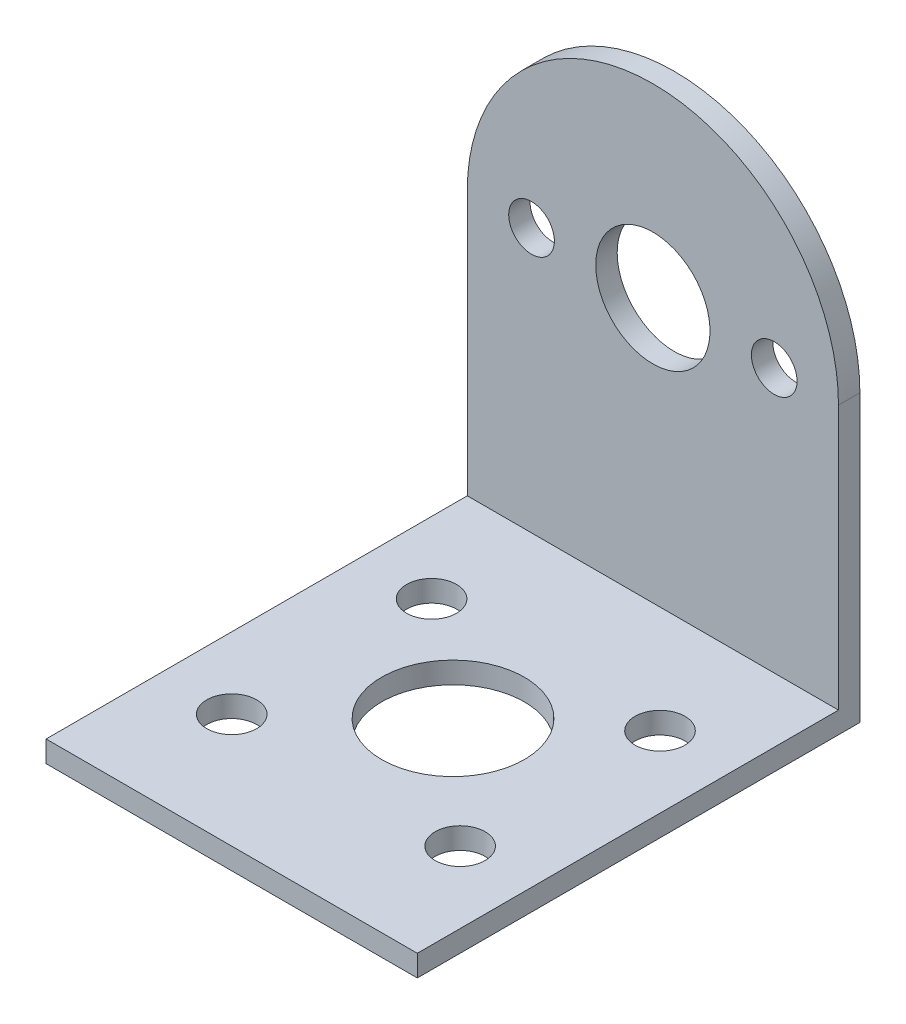
SolidWorks part; units mm, degrees
ref_plane "前视基准面" through (0, 0, 0) normal (0, 0, 1) x (1, 0, 0)
ref_plane "上视基准面" through (0, 0, 0) normal (0, 1, 0) x (1, 0, 0)
ref_plane "右视基准面" through (0, 0, 0) normal (1, 0, 0) x (0, 0, -1)
other "Configuration Table"
sketch "草图1" plane through (0, 0, 0) normal (0, 1, 0) x (1, 0, 0)
  line L1 (-13, -15.5) -> (13, -15.5)
  line L2 (-13, -15.5) -> (-13, 15.5)
  line L3 (-13, 15.5) -> (13, 15.5)
  line L4 (13, -15.5) -> (13, 15.5)
  line L5 (-13, -15.5) -> (13, 15.5) construction
  line L6 (-13, 15.5) -> (13, -15.5) construction
  line L7 (-8, -7.5) -> (8, -7.5) construction
  line L8 (-8, -7.5) -> (-8, 6.5) construction
  line L9 (-8, 6.5) -> (8, 6.5) construction
  line L10 (8, -7.5) -> (8, 6.5) construction
  line L11 (-8, -7.5) -> (8, 6.5) construction
  line L12 (-8, 6.5) -> (8, -7.5) construction
  circle A0 centre (0, 0) radius 5
  circle A1 centre (-8, 6.5) radius 1.75
  circle A2 centre (8, 6.5) radius 1.75
  circle A3 centre (8, -7.5) radius 1.75
  circle A4 centre (-8, -7.5) radius 1.75
  point P0 (0, 0)
  point P8 (0, -0.5)
  dimension "D3" = 10
  dimension "D7" = 3.5
  dimension "D8" = 3.5
  dimension "D9" = 3.5
  dimension "D10" = 3.5
  dimension "D1" = 31
  dimension "D2" = 26
  dimension "D4" = 14
  dimension "D5" = 16
  dimension "D6" = 8
extrude "凸台-拉伸1" add sketch "草图1" along normal blind 1.5
sketch "草图2" plane through (0, 0, -15.5) normal (0, 0, -1) x (-1, 0, 0)
  line L0 (0, -5.0517) -> (0, 20) construction
  line L1 (-13, -5.0517) -> (-13, 20)
  line L2 (13, -5.0517) -> (13, 20)
  line L3 (-13, 0) -> (13, 0) construction
  line L4 (-13, 20) -> (14.7135, 20) construction
  line L5 (0, 20) -> (0, 36.8001) construction
  line L6 (-13, 1.5) -> (13, 1.5) construction
  line L7 (-13, 1.5) -> (13, 1.5)
  arc A0 (-13, -5.0517) -> (13, -5.0517) centre (0, -5.0517) ccw
  arc A1 (13, 20) -> (-13, 20) centre (0, 20) ccw
  circle A2 centre (0, 20) radius 4
  circle A3 centre (-8.5, 20) radius 1.6
  circle A4 centre (8.5, 20) radius 1.6
  point P3 (0, 7.4742)
  line M11 (13, 1.5) -> (-13, 1.5)
  dimension "D2" = 13
  dimension "D3" = 8
  dimension "D4" = 3.2
  dimension "D1" = 20
  dimension "D5" = 17
extrude "凸台-拉伸2" add sketch "草图2" against normal blind 1.5 contours L2 A1 L1 A2 A3 A4 M11
